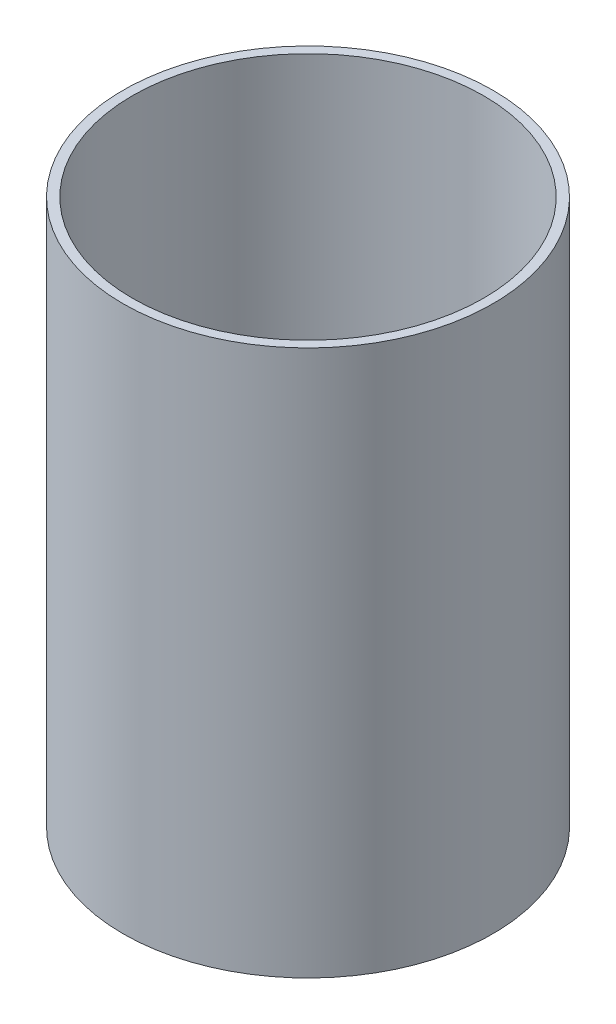
SolidWorks part; units mm, degrees
ref_plane "Front Plane" through (0, 0, 0) normal (0, 0, 1) x (1, 0, 0)
ref_plane "Top Plane" through (0, 0, 0) normal (0, 1, 0) x (1, 0, 0)
ref_plane "Right Plane" through (0, 0, 0) normal (1, 0, 0) x (0, 0, -1)
sketch "Sketch1" plane through (0, 0, 0) normal (0, 1, 0) x (1, 0, 0)
  circle A0 centre (0, 0) radius 49.911
  circle A2 centre (0, 0) radius 47.371
  dimension "D1" = 2.54
  dimension "D2" = 99.822
extrude "Boss-Extrude1" add sketch "Sketch1" along normal blind 144.7292
sketch "Sketch2" plane through (0, 0, 0) normal (0, -1, 0) x (1, 0, 0)
  circle A0 centre (0, 0) radius 49.911
  circle A1 centre (0, 0) radius 49.911 construction
extrude "Boss-Extrude2" add sketch "Sketch2" along normal blind 2.54
